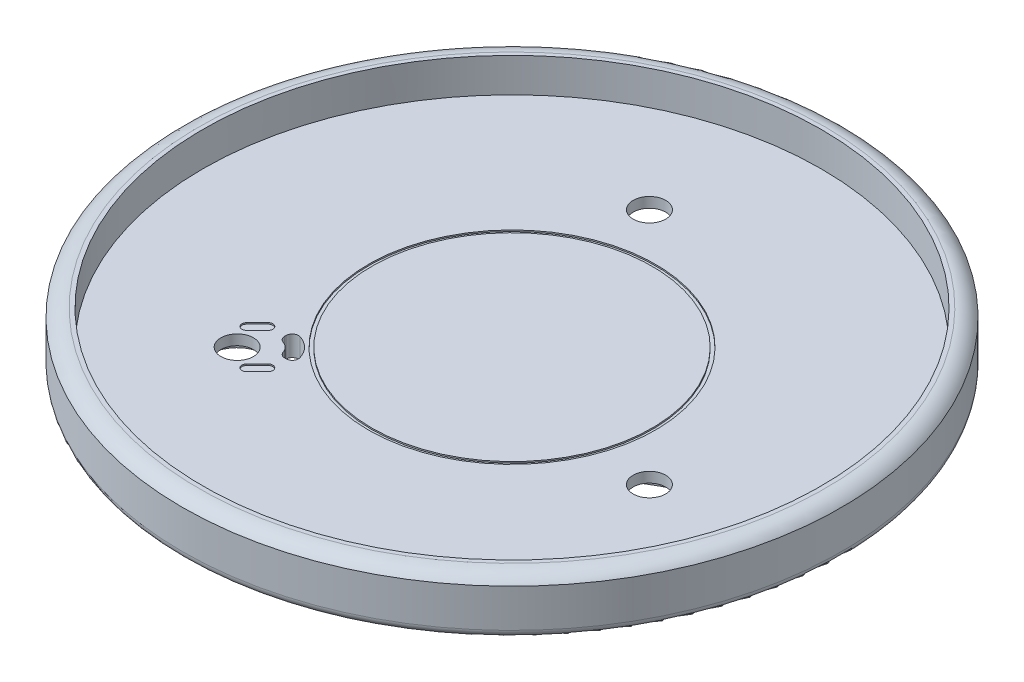
SolidWorks part; units mm, degrees
ref_plane "前视基准面" through (0, 0, 0) normal (0, 0, 1) x (1, 0, 0)
ref_plane "上视基准面" through (0, 0, 0) normal (0, 1, 0) x (1, 0, 0)
ref_plane "右视基准面" through (0, 0, 0) normal (1, 0, 0) x (0, 0, -1)
sketch "草图1" plane through (0, 0, 0) normal (0, 1, 0) x (1, 0, 0)
  circle A0 centre (0, 0) radius 45.2
  circle A1 centre (0, 0) radius 20.5 construction
  dimension "D1" = 90.4
  dimension "D2" = 41
extrude "凸台-拉伸1" add sketch "草图1" along normal blind 3
sketch "草图3" plane through (0, 0, 0) normal (0, -1, 0) x (1, 0, 0)
  circle A0 centre (0, 0) radius 48.2
  circle A1 centre (0, 0) radius 45.2 construction
  circle A2 centre (0, 0) radius 45.2
  dimension "D1" = 3
extrude "凸台-拉伸2" add sketch "草图3" against normal blind 8
sketch "草图4" plane through (0, 3, 0) normal (0, 1, 0) x (1, 0, 0)
  line L0 (-37.8336, 0) -> (34.4444, 0) construction
  line L1 (0, 37.4001) -> (0, -32.3556) construction
  circle A0 centre (0, 0) radius 20.5
  circle A1 centre (0, 0) radius 21
  dimension "D1" = 41
  dimension "D2" = 42
extrude "切除-拉伸1" cut sketch "草图4" against normal blind 0.2
sketch "草图5" plane through (0, 0, 0) normal (1, 0, 0) x (0, 0, -1)
  line L0 (48.2, 6.8) -> (48.2, 8)
  line L2 (48.2, 8) -> (45.8, 8)
  line L3 (45.2, 8) -> (-45.2, 8) construction
  line L4 (0, 0) -> (0, 12.9368)
  arc A0 (45.8, 8) -> (48.2, 6.8) centre (45.8, 5) cw
  dimension "D1" = 1.2
  dimension "D2" = 2.4
revolve "切除-旋转1" cut sketch "草图5" angle 360 about L4
fillet "圆角2" radius 1.2 1 edges at (0, 0, -48.2)
sketch "草图6" plane through (0, 0, 0) normal (0, -1, 0) x (1, 0, 0)
  line L0 (-29.5028, 0) -> (27.9284, 0) construction
  line L1 (0, 23.6501) -> (0, -22.1442) construction
  line L2 (-26, 23.2) -> (-23.8509, 18.3731)
  line L3 (-24, 26) -> (-18, 26)
  line L4 (-26, 24) -> (-26, 19)
  line L5 (-20.1967, 16) -> (-18, 16)
  line L6 (-16, 20.1967) -> (-16, 18)
  line L7 (-23.2, 26) -> (-18.3731, 23.8509)
  line L8 (33.0918, 10.9167) -> (27.837, 11.469)
  line L9 (33.7846, 10.5167) -> (29.4545, 13.0167)
  line L10 (34.5167, 7.7846) -> (31.5167, 2.5885)
  line L11 (34.1167, 7.0918) -> (29.842, 3.9861)
  line L12 (25.4909, 3.758) -> (23.5885, 4.8564)
  line L13 (23.9548, 9.4909) -> (22.8564, 7.5885)
  line L14 (-7.0918, -34.1167) -> (-3.9861, -29.842)
  line L15 (-7.7846, -34.5167) -> (-3.4545, -32.0167)
  line L16 (-10.5167, -33.7846) -> (-13.5167, -28.5885)
  line L17 (-10.9167, -33.0918) -> (-11.469, -27.837)
  line L18 (-9.4909, -23.9548) -> (-7.5885, -22.8564)
  line L19 (-3.758, -25.4909) -> (-4.8564, -23.5885)
  arc A0 (-26, 24) -> (-24, 26) centre (-24, 24) cw
  arc A1 (-18, 16) -> (-16, 18) centre (-18, 18) ccw
  arc A2 (-16, 20.1967) -> (-18.3731, 23.8509) centre (-20, 20.1967) ccw
  arc A3 (-23.8509, 18.3731) -> (-20.1967, 16) centre (-20.1967, 20) ccw
  arc A4 (33.7846, 10.5167) -> (34.5167, 7.7846) centre (32.7846, 8.7846) cw
  arc A5 (25.4909, 3.758) -> (29.842, 3.9861) centre (27.4909, 7.2221) ccw
  arc A6 (22.8564, 7.5885) -> (23.5885, 4.8564) centre (24.5885, 6.5885) ccw
  arc A7 (27.837, 11.469) -> (23.9548, 9.4909) centre (27.4189, 7.4909) ccw
  arc A8 (-7.7846, -34.5167) -> (-10.5167, -33.7846) centre (-8.7846, -32.7846) cw
  arc A9 (-9.4909, -23.9548) -> (-11.469, -27.837) centre (-7.4909, -27.4189) ccw
  arc A10 (-4.8564, -23.5885) -> (-7.5885, -22.8564) centre (-6.5885, -24.5885) ccw
  arc A11 (-3.9861, -29.842) -> (-3.758, -25.4909) centre (-7.2221, -27.4909) ccw
  point P11 (-26, 26)
  point P18 (-16, 16)
  point P58 (0, 0)
  dimension "D5" = 2
  dimension "D10" = 2
  dimension "D3" = 4
  dimension "D1" = 16
  dimension "D2" = 16
  dimension "D4" = 10
  dimension "D6" = 24
  dimension "D7" = 24
  dimension "D8" = 0.8
  dimension "D9" = 0.8
  dimension "D11" = 10
  dimension "D12" = 3
extrude "切除-拉伸2" cut sketch "草图6" against normal blind 1.5 contours L14 A11 L19 A10 L18 A9 L17 L16 A8 L15 | L8 A7 L13 A6 L12 A5 L11 L10 A4 L9 | L2 A3 L5 A1 L6 A2 L7 L3 A0 L4
sketch "草图7" plane through (0, 0, 0) normal (0, -1, 0) x (1, 0, 0)
  line L0 (0, 0) -> (-25.4142, 25.4142) construction
  line L1 (-18, 15.0335) -> (-18, 15.2432)
  line L2 (-15.0335, 18) -> (-15.2432, 18)
  arc A0 (-24, 26) -> (-26, 24) centre (-24, 24) ccw construction
  arc A3 (-18, 16) -> (-16, 18) centre (-18, 18) ccw construction
  arc A4 (-17.3793, 16.0988) -> (-16.0988, 17.3793) centre (-18, 18) ccw
  arc A5 (-16.8387, 14.1723) -> (-14.1723, 16.8387) centre (-18, 18) ccw
  arc A6 (-18, 16) -> (-16, 18) centre (-18, 18) ccw construction
  arc A7 (-18, 15.2432) -> (-17.3793, 16.0988) centre (-17.1, 15.2432) cw
  arc A8 (-18, 14) -> (-14, 18) centre (-18, 18) ccw construction
  arc A9 (-18, 15.0335) -> (-16.8387, 14.1723) centre (-17.1, 15.0335) ccw
  arc A10 (-14.1723, 16.8387) -> (-15.0335, 18) centre (-15.0335, 17.1) ccw
  arc A11 (-15.2432, 18) -> (-16.0988, 17.3793) centre (-15.2432, 17.1) ccw
  dimension "D2" = 0.9
  dimension "D1" = 2
extrude "切除-拉伸3" cut sketch "草图7" against normal blind 10
sketch "草图8" plane through (0, 3, 0) normal (0, 1, 0) x (1, 0, 0)
  line L0 (0, 0) -> (-24.3102, -24.3102) construction
  line L1 (-16.7808, -22.0134) -> (-15.2252, -20.4578) construction
  line L2 (-17.2758, -21.5184) -> (-15.7201, -19.9628)
  line L3 (-16.2858, -22.5084) -> (-14.7302, -20.9527)
  line L4 (-22.0134, -16.7808) -> (-20.4578, -15.2252) construction
  line L5 (-21.5184, -17.2758) -> (-19.9628, -15.7201)
  line L6 (-22.5084, -16.2858) -> (-20.9527, -14.7302)
  arc A0 (-17.2758, -21.5184) -> (-16.2858, -22.5084) centre (-16.7808, -22.0134) ccw
  arc A1 (-14.7302, -20.9527) -> (-15.7201, -19.9628) centre (-15.2252, -20.4578) ccw
  arc A2 (-16.0988, -17.3793) -> (-17.3793, -16.0988) centre (-18, -18) ccw construction
  arc A3 (-16.0988, -17.3793) -> (-17.3793, -16.0988) centre (-18, -18) ccw
  arc A4 (-21.5184, -17.2758) -> (-22.5084, -16.2858) centre (-22.0134, -16.7808) cw
  arc A5 (-20.9527, -14.7302) -> (-19.9628, -15.7201) centre (-20.4578, -15.2252) cw
  point P5 (-16.003, -21.2356)
  point P16 (-21.2356, -16.003)
  dimension "D2" = 0.7
  dimension "D1" = 2.2
  dimension "D3" = 3
  dimension "D4" = 3.2
extrude "切除-拉伸4" cut sketch "草图8" against normal blind 0.2 contours A5 L6 A4 L5 | L3 A1 L2 A0
sketch "草图9" plane through (0, 3, 0) normal (0, 1, 0) x (1, 0, 0)
  line L0 (-20, -20.1967) -> (-20.1967, -20)
  line L1 (0, 0) -> (-20.0984, -20.0984) construction
  circle A0 centre (-20.0984, -20.0984) radius 2.38
  circle A1 centre (-7.3565, 27.4549) radius 2.38
  circle A2 centre (27.4549, -7.3565) radius 2.38
  dimension "D1" = 4.76
  dimension "D3" = 28.4234
  dimension "D2" = 3
extrude "切除-拉伸5" cut sketch "草图9" against normal blind 10
sketch "草图10" plane through (0, 0, 0) normal (0, -1, 0) x (1, 0, 0)
  line L0 (0, 0) -> (-15.1716, 15.1716) construction
  line L1 (-21.7279, -6.5563) -> (6.5563, 21.7279) construction
  arc A0 (-16.8387, 14.1723) -> (-14.1723, 16.8387) centre (-18, 18) ccw construction
  text T0 "<b>09</b>" font "JetBrains Mono" height 9
  point P10 (-7.5858, 7.5858)
  dimension "D1" = 20
  dimension "D2" = 40
extrude "切除-拉伸6" cut sketch "草图10" against normal blind 0.8
